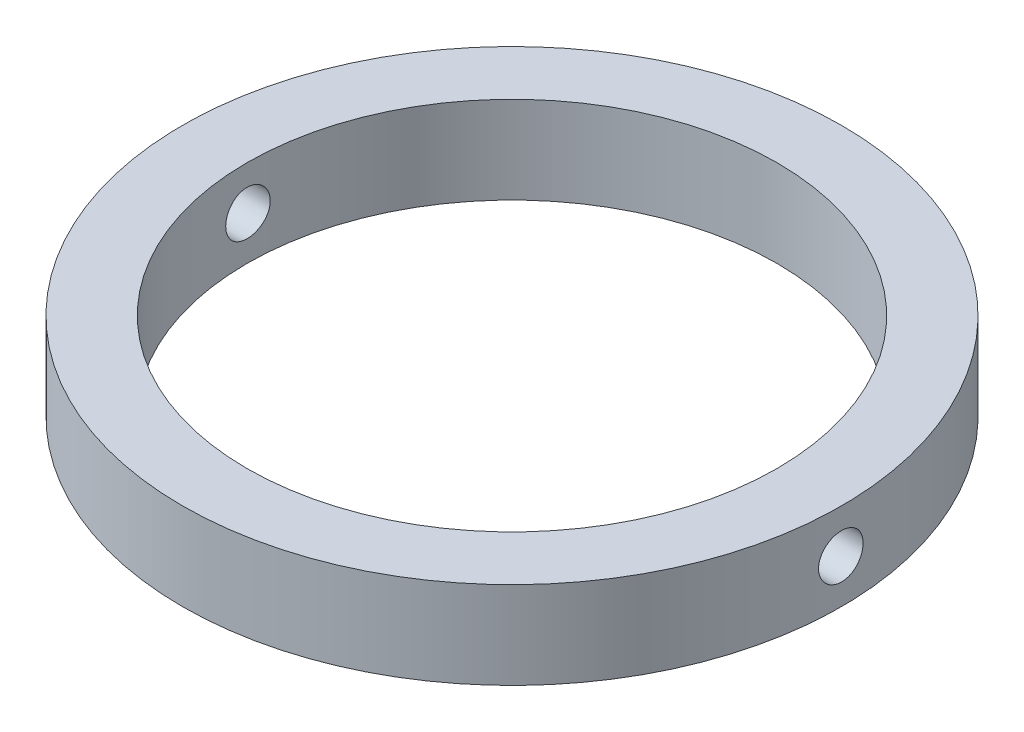
SolidWorks part; units mm, degrees
material "5052-H38, Rod (SS)"
ref_plane "Front Plane" through (0, 0, 0) normal (0, 0, 1) x (1, 0, 0)
ref_plane "Top Plane" through (0, 0, 0) normal (0, 1, 0) x (1, 0, 0)
ref_plane "Right Plane" through (0, 0, 0) normal (1, 0, 0) x (0, 0, -1)
sketch "Sketch1" plane through (0, 0, 0) normal (0, 1, 0) x (1, 0, 0)
  circle A0 centre (0, 0) radius 30.35
  circle A1 centre (0, 0) radius 37.75
  dimension "D1" = 60.7
  dimension "D2" = 7.4
extrude "Boss-Extrude1" add sketch "Sketch1" along normal blind 10
ref_plane "Plane2" through (-37.75, 0, 0) normal (-1, 0, 0) x (0, 0, 1)
sketch "Sketch4" plane through (-37.75, 0, 0) normal (-1, 0, 0) x (0, 0, 1)
  line L0 (0, 10) -> (0, 0)
  line L1 (37.75, 10) -> (-37.75, 10) construction
  circle A0 centre (0, 5) radius 2.55
  dimension "D1" = 5.1
extrude "Cut-Extrude2" cut sketch "Sketch4" against normal blind 93 contours A0
